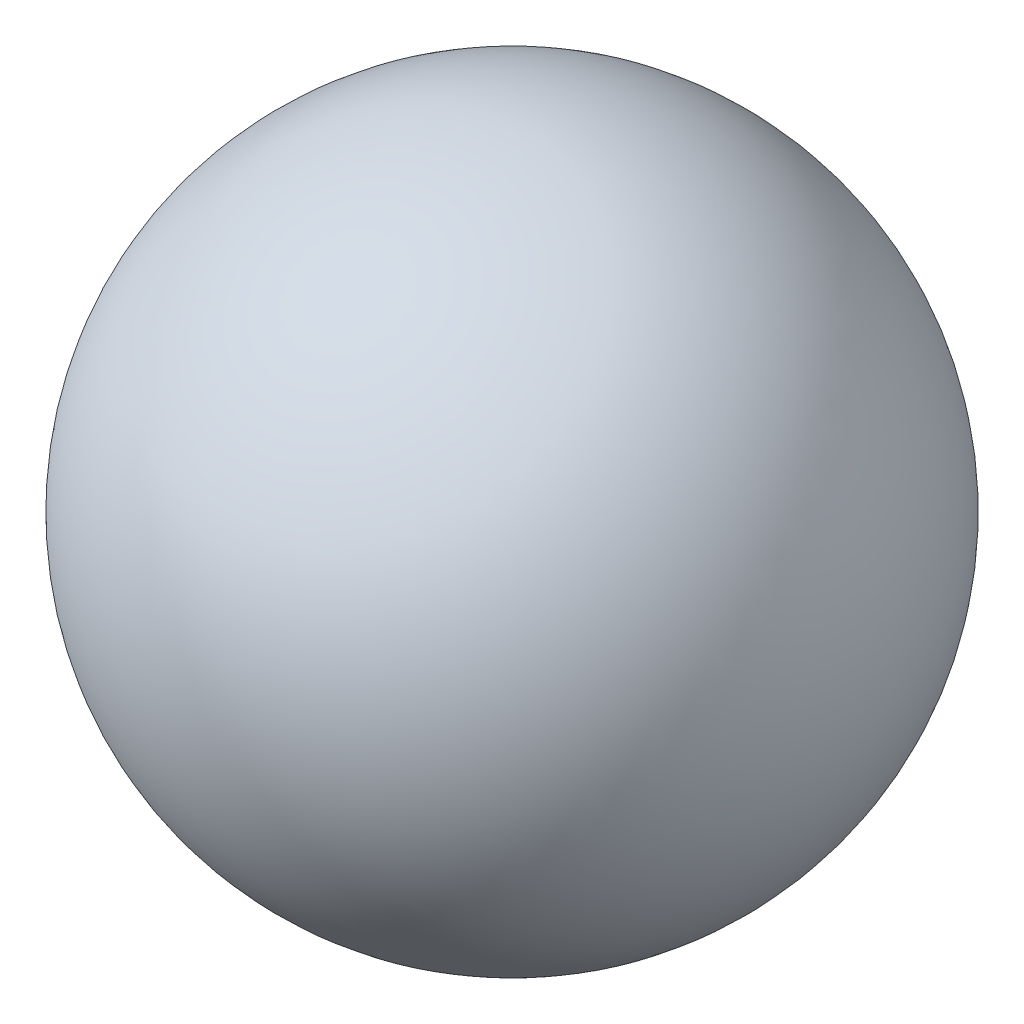
SolidWorks part; units mm, degrees
ref_plane "Front Plane" through (0, 0, 0) normal (0, 0, 1) x (1, 0, 0)
ref_plane "Top Plane" through (0, 0, 0) normal (0, 1, 0) x (1, 0, 0)
ref_plane "Right Plane" through (0, 0, 0) normal (1, 0, 0) x (0, 0, -1)
sketch "Sketch1" plane through (0, 0, 0) normal (0, 0, 1) x (1, 0, 0)
  line L0 (0, 25.4) -> (0, -25.4)
  arc A0 (0, 25.4) -> (0, -25.4) centre (0, 0) ccw
  dimension "D1" = 25.4
revolve "Revolve1" add sketch "Sketch1" angle 360 about L0
